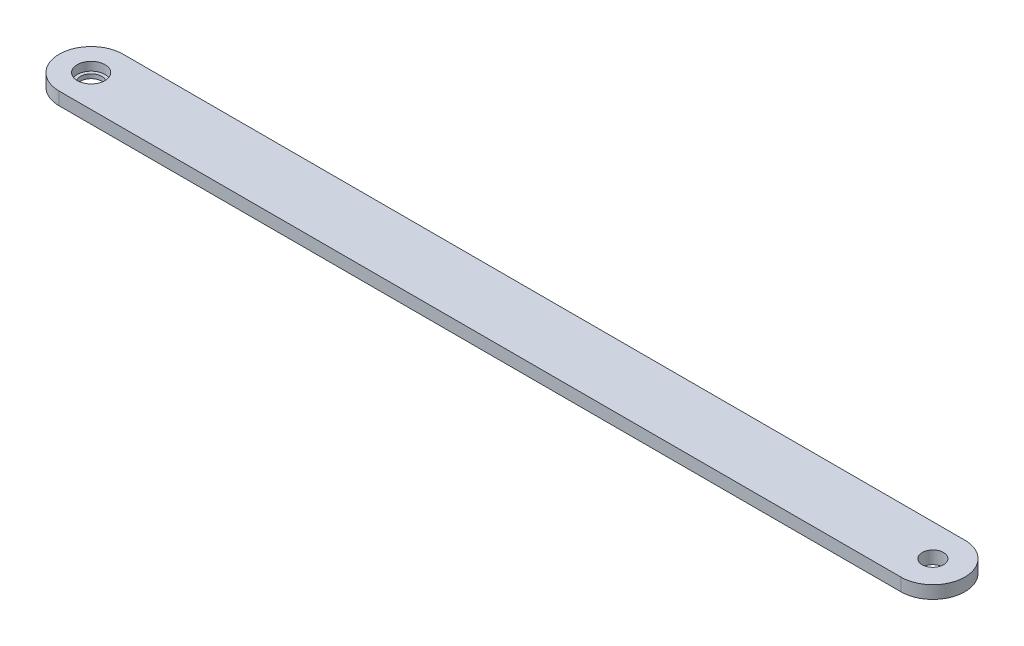
SolidWorks part; units mm, degrees
ref_plane "Front Plane" through (0, 0, 0) normal (0, 0, 1) x (1, 0, 0)
ref_plane "Top Plane" through (0, 0, 0) normal (0, 1, 0) x (1, 0, 0)
ref_plane "Right Plane" through (0, 0, 0) normal (1, 0, 0) x (0, 0, -1)
sketch "Sketch2" plane through (0, 0, 0) normal (0, 1, 0) x (1, 0, 0)
  line L1 (-45, 15) -> (350, 15)
  line L3 (-45, -15) -> (350, -15)
  arc A0 (-45, 15) -> (-45, -15) centre (-45, 0) ccw
  arc A1 (350, -15) -> (350, 15) centre (350, 0) ccw
  circle A2 centre (-45, 0) radius 5
  circle A3 centre (350, 0) radius 5
  point P0 (0, 0)
  point P7 (0, 0)
  point P9 (0, 0)
  point P12 (0, 0)
extrude "Boss-Extrude1" add sketch "Sketch2" along normal blind 6
sketch "Sketch4" plane through (0, 6, 0) normal (0, 1, 0) x (1, 0, 0)
  circle A0 centre (-45, 0) radius 6.5
extrude "Cut-Extrude2" cut sketch "Sketch4" against normal blind 4
